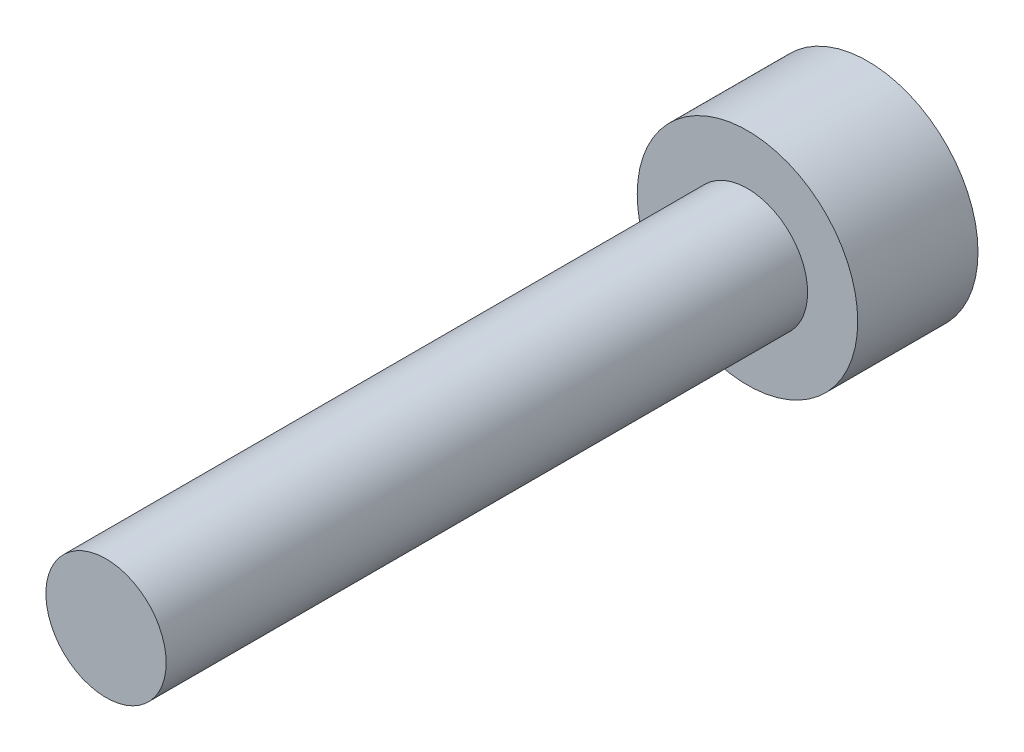
SolidWorks part; units mm, degrees
ref_plane "前视基准面" through (0, 0, 0) normal (0, 0, 1) x (1, 0, 0)
ref_plane "上视基准面" through (0, 0, 0) normal (0, 1, 0) x (1, 0, 0)
ref_plane "右视基准面" through (0, 0, 0) normal (1, 0, 0) x (0, 0, -1)
other "Configuration Table"
sketch "草图1" plane through (0, 0, 0) normal (0, 0, 1) x (1, 0, 0)
  circle A0 centre (0, 0) radius 1.5
extrude "M3螺杆_螺纹简化" add sketch "草图1" along normal blind 16
sketch "草图2" plane through (0, 0, 0) normal (0, 0, 1) x (1, 0, 0)
  circle A0 centre (0, 0) radius 2.75
extrude "内六角圆柱头" add sketch "草图2" against normal blind 3
sketch "草图3" plane through (0, 0, -3) normal (0, 0, -1) x (-1, 0, 0)
  line L0 (1.4434, 0) -> (0.7217, 1.25)
  line L1 (0.7217, 1.25) -> (-0.7217, 1.25)
  line L2 (-0.7217, 1.25) -> (-1.4434, 0)
  line L3 (-1.4434, 0) -> (-0.7217, -1.25)
  line L4 (-0.7217, -1.25) -> (0.7217, -1.25)
  line L5 (0.7217, -1.25) -> (1.4434, 0)
extrude "内六角扳手孔" cut sketch "草图3" against normal blind 1.3
